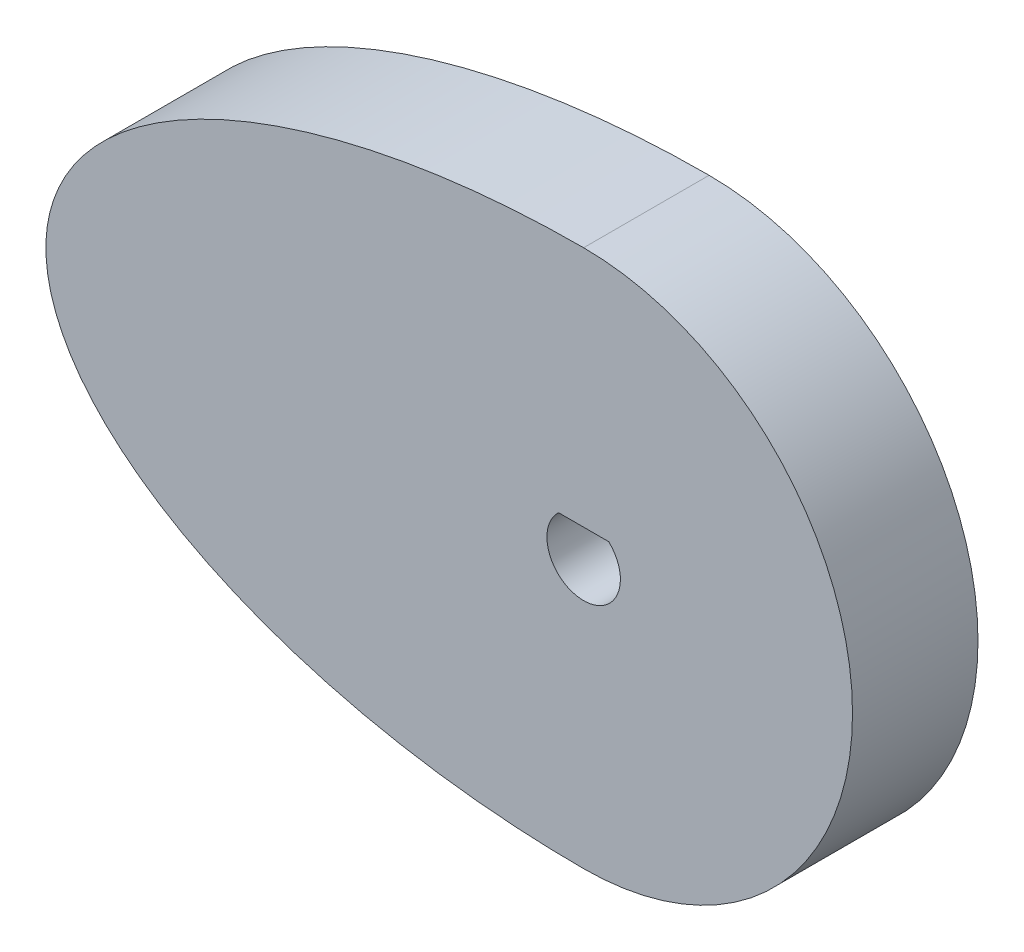
SolidWorks part; units mm, degrees
ref_plane "Front Plane" through (0, 0, 0) normal (0, 0, 1) x (1, 0, 0)
ref_plane "Top Plane" through (0, 0, 0) normal (0, 1, 0) x (1, 0, 0)
ref_plane "Right Plane" through (0, 0, 0) normal (1, 0, 0) x (0, 0, -1)
sketch "Sketch1" plane through (0, 0, 0) normal (0, 0, 1) x (1, 0, 0)
  arc A0 (0, -30) -> (0, 30) centre (0, 0) ccw
  ellipse E0 centre (0, 0) end of major axis (60, 0) minor radius 30 (0, 30) -> (0, -30) ccw
extrude "Boss-Extrude2" add sketch "Sketch1" along normal blind 14
sketch "Sketch2" plane through (0, 0, 0) normal (0, 0, -1) x (-1, 0, 0)
  line L1 (-2.7946, 3) -> (2.7946, 3)
  arc A0 (-2.7946, 3) -> (2.7946, 3) centre (0, 0) ccw
  dimension "D1" = 3
extrude "Cut-Extrude1" cut sketch "Sketch2" against normal up to surface (14 mm away) up to face at (-15, 0, 14)
